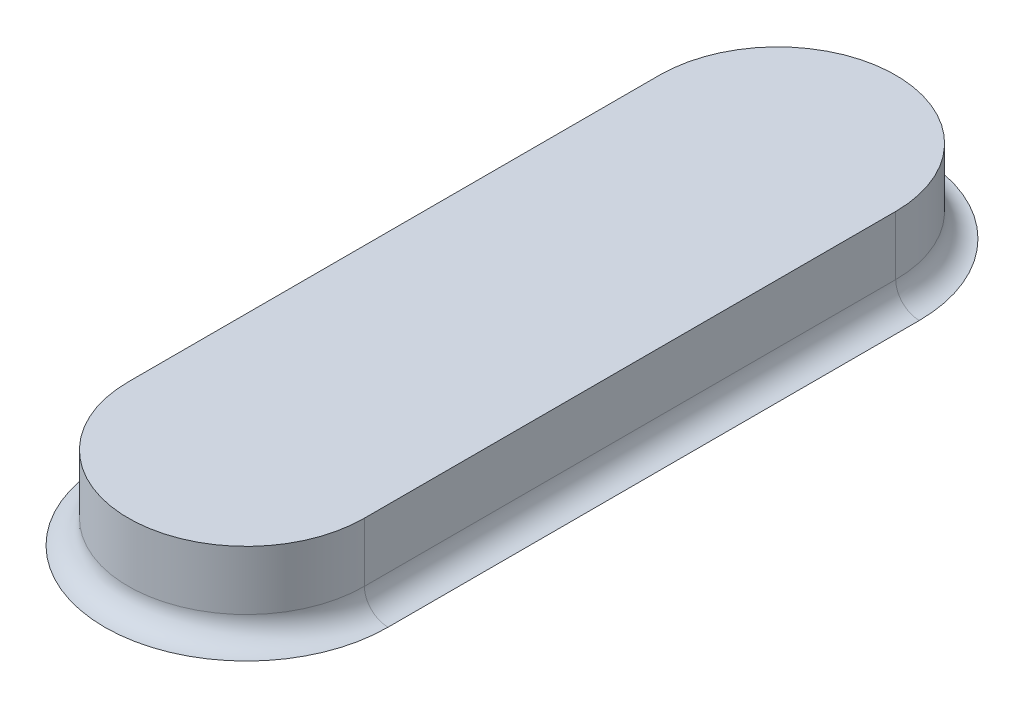
SolidWorks part; units mm, degrees
ref_plane "Front Plane" through (0, 0, 0) normal (0, 0, 1) x (1, 0, 0)
ref_plane "Top Plane" through (0, 0, 0) normal (0, 1, 0) x (1, 0, 0)
ref_plane "Right Plane" through (0, 0, 0) normal (1, 0, 0) x (0, 0, -1)
sketch "Sketch1" plane through (0, 0, 0) normal (0, 1, 0) x (1, 0, 0)
  line L1 (13, 18) -> (-13, 18)
  line L2 (13, 18) -> (13, -18)
  line L3 (13, -18) -> (-13, -18)
  line L4 (-13, 18) -> (-13, -18)
  line L5 (13, 18) -> (-13, -18) construction
  line L6 (13, -18) -> (-13, 18) construction
  point P0 (0, 0)
  dimension "D1" = 26
  dimension "D2" = 36
extrude "Boss-Extrude1" add sketch "Sketch1" along normal blind 10
sketch "Sketch2" plane through (0, 10, 0) normal (0, 1, 0) x (1, 0, 0)
  line L0 (10, 18) -> (10, -4.5)
  line L1 (13, 18) -> (-13, 18) construction
  line L2 (-10, -4.5) -> (-10, 18)
  line L3 (-10, 18) -> (10, 18)
  arc A0 (10, -4.5) -> (-10, -4.5) centre (0, -4.5) cw
  dimension "D1" = 20
  dimension "D2" = 22.5
extrude "Boss-Extrude2" add sketch "Sketch2" along normal blind 7
fillet "Fillet1" radius 2 3 edges at (-10, 10, -6.75) (0, 10, 14.5) (10, 10, -6.75)
sketch "Sketch3" plane through (0, 0, 18) normal (0, 0, 1) x (1, 0, 0)
  line L0 (-13, 10) -> (13, 10) construction
  line L1 (-13, 10) -> (13, 10)
split "Split1" trim tools "Sketch3" bodies to split 102 resulting bodies 103
mirror "Mirror1" about plane through (13, 10, -18) normal (0, 0, 1) of bodies 103
sketch "Orientation Sketch" plane through (0, 10, 0) normal (0, -1, 0) x (-1, 0, 0)
  line L0 (12, -4.5) -> (12, 40.5) construction
  line L1 (-12, 40.5) -> (-12, -4.5) construction
  line L2 (12, -4.5) -> (12, 40.5)
  line L3 (-12, 40.5) -> (-12, -4.5)
  arc A0 (12, 40.5) -> (-12, 40.5) centre (0, 40.5) ccw construction
  arc A1 (-12, -4.5) -> (12, -4.5) centre (0, -4.5) ccw construction
  arc A2 (12, 40.5) -> (-12, 40.5) centre (0, 40.5) ccw
  arc A3 (-12, -4.5) -> (12, -4.5) centre (0, -4.5) ccw
  point P6 (0, 18)
other "FormTool1"
